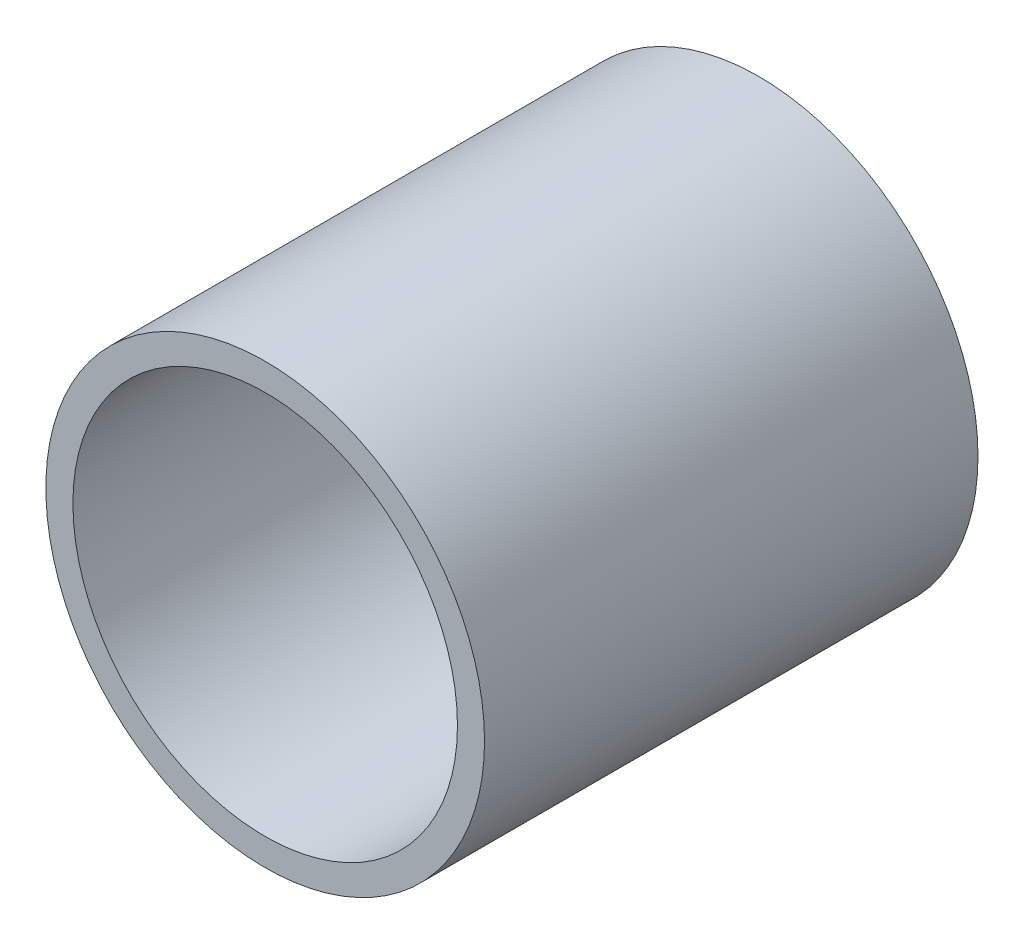
SolidWorks part; units mm, degrees
ref_plane "Front Plane" through (0, 0, 0) normal (0, 0, 1) x (1, 0, 0)
ref_plane "Top Plane" through (0, 0, 0) normal (0, 1, 0) x (1, 0, 0)
ref_plane "Right Plane" through (0, 0, 0) normal (1, 0, 0) x (0, 0, -1)
sketch "Sketch1" plane through (0, 0, 0) normal (0, 0, 1) x (1, 0, 0)
  circle A0 centre (0, 0) radius 44.45
  dimension "Pipe OD" = 88.9
extrude "Extrude-Thin1" add sketch "Sketch1" along normal mid plane 100 thin thin type one direction reverse wall 5.4864
